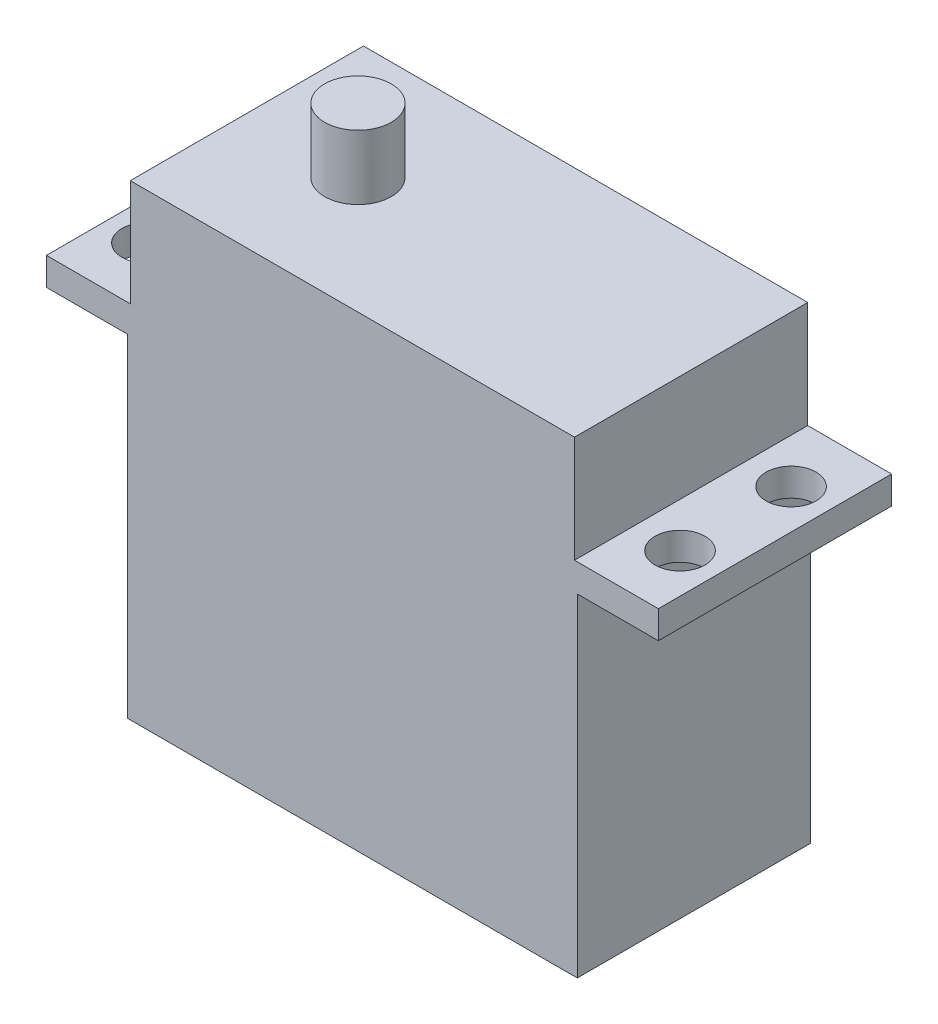
SolidWorks part; units mm, degrees
ref_plane "前视基准面" through (0, 0, 0) normal (0, 0, 1) x (1, 0, 0)
ref_plane "上视基准面" through (0, 0, 0) normal (0, 1, 0) x (1, 0, 0)
ref_plane "右视基准面" through (0, 0, 0) normal (1, 0, 0) x (0, 0, -1)
sketch "草图1" plane through (0, 0, 0) normal (0, 1, 0) x (1, 0, 0)
  line L1 (-20.25, -10.5) -> (20.25, -10.5)
  line L2 (-20.25, -10.5) -> (-20.25, 10.5)
  line L3 (-20.25, 10.5) -> (20.25, 10.5)
  line L4 (20.25, -10.5) -> (20.25, 10.5)
  line L5 (-20.25, -10.5) -> (20.25, 10.5) construction
  line L6 (-20.25, 10.5) -> (20.25, -10.5) construction
  point P0 (0, 0)
  point P6 (0, 0)
  dimension "D1" = 40.5
  dimension "D2" = 21
extrude "凸台-拉伸1" add sketch "草图1" along normal blind 32.45
sketch "草图2" plane through (0, 32.45, 0) normal (0, 1, 0) x (1, 0, 0)
  line L0 (0, -55) -> (0, 55) construction
  line L1 (20.25, -10.5) -> (27.55, -10.5)
  line L2 (20.25, -10.5) -> (20.25, 10.5)
  line L3 (20.25, 10.5) -> (27.55, 10.5)
  line L4 (27.55, -10.5) -> (27.55, 10.5)
  line L5 (-55, 0) -> (55, 0) construction
  line L6 (-27.55, -10.5) -> (-27.55, 10.5)
  line L7 (-20.25, 10.5) -> (-27.55, 10.5)
  line L8 (-20.25, -10.5) -> (-20.25, 10.5)
  line L9 (-20.25, -10.5) -> (-27.55, -10.5)
  circle A0 centre (24, 5) radius 2.25
  circle A1 centre (24, -5) radius 2.25
  circle A2 centre (-24, -5) radius 2.25
  circle A3 centre (-24, 5) radius 2.25
  dimension "D3" = 4.5
  dimension "D1" = 27.55
  dimension "D2" = 21
  dimension "D4" = 24
  dimension "D5" = 5
extrude "凸台-拉伸2" add sketch "草图2" against normal blind 2.5
sketch "草图3" plane through (0, 32.45, 0) normal (0, 1, 0) x (1, 0, 0)
  line L0 (27.55, 10.5) -> (-27.55, 10.5) construction
  line L1 (-20, -10.5) -> (20, -10.5)
  line L2 (-20, -10.5) -> (-20, 10.5)
  line L3 (-20, 10.5) -> (20, 10.5)
  line L4 (20, -10.5) -> (20, 10.5)
  line L5 (-20, -10.5) -> (20, 10.5) construction
  line L6 (-20, 10.5) -> (20, -10.5) construction
  point P0 (0, 0)
  dimension "D1" = 40
extrude "凸台-拉伸3" add sketch "草图3" along normal blind 9.6
sketch "草图4" plane through (0, 42.05, 0) normal (0, 1, 0) x (1, 0, 0)
  line L0 (-17.8475, 0) -> (17.8475, 0) construction
  circle A0 centre (-10, 0) radius 3
  circle A1 centre (-24, 5) radius 2.25 construction
  dimension "D1" = 6
  dimension "D2" = 14
extrude "凸台-拉伸4" add sketch "草图4" along normal blind 5.8
